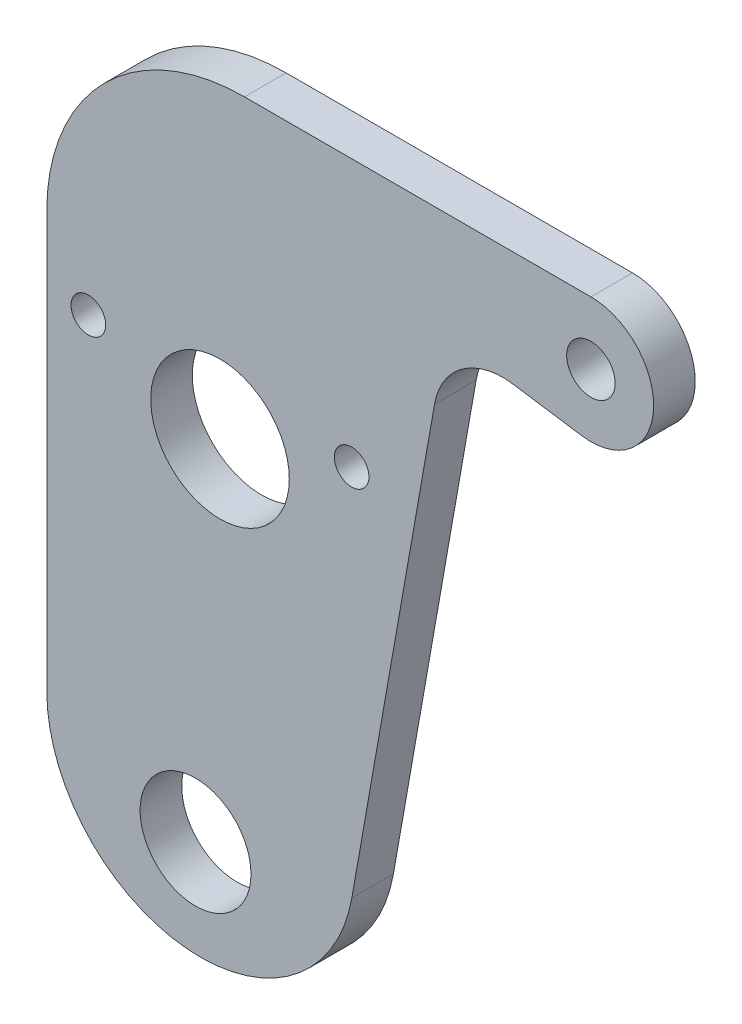
SolidWorks part; units mm, degrees
ref_plane "Front Plane" through (0, 0, 0) normal (0, 0, 1) x (1, 0, 0)
ref_plane "Top Plane" through (0, 0, 0) normal (0, 1, 0) x (1, 0, 0)
ref_plane "Right Plane" through (0, 0, 0) normal (1, 0, 0) x (0, 0, -1)
sketch "Sketch3" plane through (0, 0, 0) normal (0, 0, 1) x (1, 0, 0)
  line L0 (-12.5, -15) -> (-12.5, 15)
  line L1 (1.7668, 29.2668) -> (26.7668, 29.2668)
  line L2 (26.095, 20.2608) -> (21.1503, 21.0025)
  line L3 (15.4845, 16.9261) -> (9.5155, -16.9261)
  line L4 (-12.5, 0) -> (12.5, 0) construction
  line L5 (-2.3747, -26.0498) -> (-1.408, -15) construction
  arc A0 (-12.5, 15) -> (1.7668, 29.2668) centre (1.7668, 15) cw
  arc A1 (26.7668, 29.2668) -> (26.095, 20.2608) centre (26.7668, 24.7387) cw
  arc A2 (21.1503, 21.0025) -> (15.4845, 16.9261) centre (20.4086, 16.0579) ccw
  arc A3 (-12.5, -15) -> (9.5155, -16.9261) centre (-1.408, -15) ccw
  circle A4 centre (-1.7646, -19.0764) radius 4
  point P18 (-1.9862, -21.6085)
  dimension "D3" = 10
  dimension "D8" = 5
  dimension "D10" = 8
  dimension "D1" = 25
  dimension "D2" = 30
  dimension "D5" = 25
  dimension "D6" = 5
  dimension "D9" = 7
extrude "Boss-Extrude4" add sketch "Sketch3" along normal blind 3
sketch "Sketch5" plane through (0, 0, 3) normal (0, 0, 1) x (1, 0, 0)
  line L0 (-9.5, 10) -> (9.5, 10) construction
  line L1 (0, 10) -> (0, 7) construction
  line L2 (0, 7) -> (0, 0) construction
  circle A0 centre (-9.5, 10) radius 1.25
  circle A1 centre (9.5, 10) radius 1.25
  circle A2 centre (0, 7) radius 5
  dimension "D2" = 10
  dimension "D3" = 2.5
  dimension "D1" = 19
  dimension "D4" = 3
  dimension "D5" = 7
extrude "Cut-Extrude2" cut sketch "Sketch5" against normal through all
sketch "Sketch6" plane through (0, 0, 3) normal (0, 0, 1) x (1, 0, 0)
  circle A0 centre (26.7668, 24.7387) radius 1.75
  dimension "D1" = 3.5
extrude "Cut-Extrude3" cut sketch "Sketch6" against normal through all
